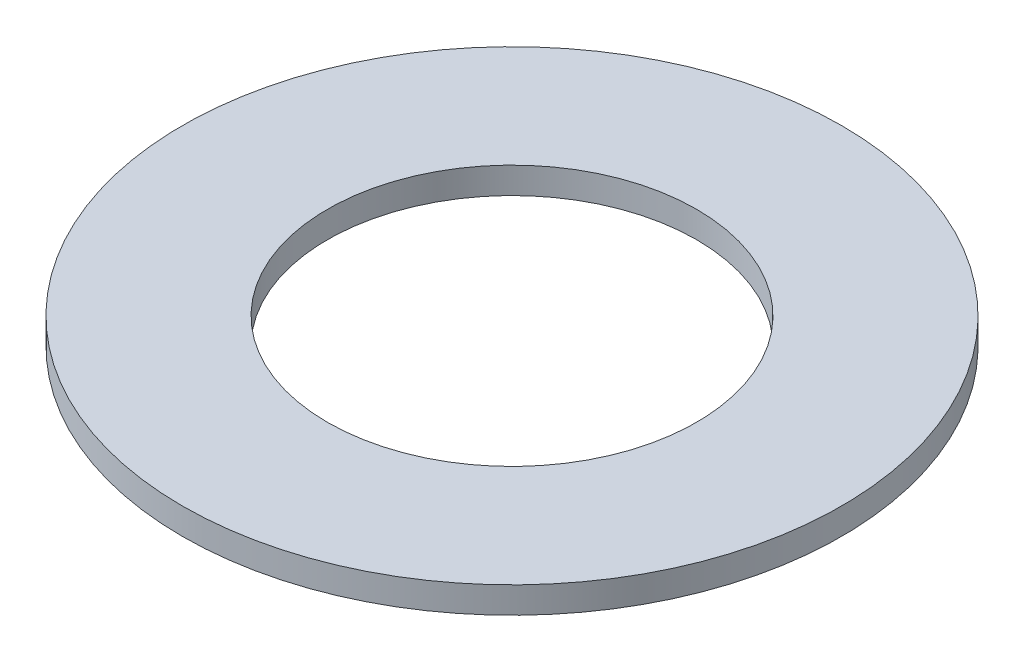
SolidWorks part; units mm, degrees
material "ABS"
ref_plane "Alzado" through (0, 0, 0) normal (0, 0, 1) x (1, 0, 0)
ref_plane "Planta" through (0, 0, 0) normal (0, 1, 0) x (1, 0, 0)
ref_plane "Vista lateral" through (0, 0, 0) normal (1, 0, 0) x (0, 0, -1)
sketch "Croquis1" plane through (0, 0, 0) normal (0, 1, 0) x (1, 0, 0)
  circle A0 centre (0, 0) radius 25
  dimension "D1" = 50
extrude "Saliente-Extruir1" add sketch "Croquis1" along normal blind 2
sketch "Croquis2" plane through (0, 2, 0) normal (0, 1, 0) x (1, 0, 0)
  circle A0 centre (0, 0) radius 14
  dimension "D1" = 28
extrude "Cortar-Extruir1" cut sketch "Croquis2" against normal through all
